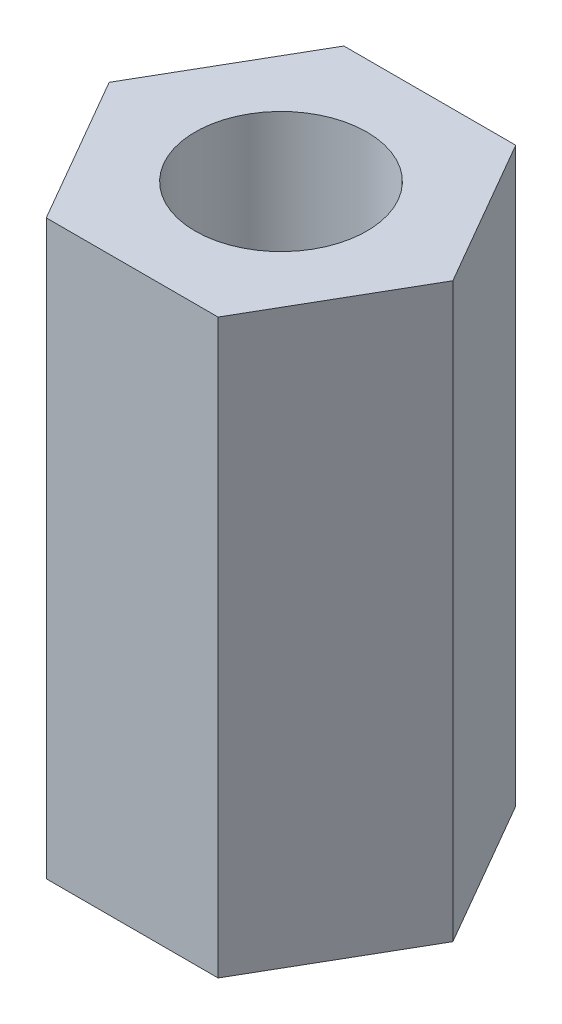
SolidWorks part; units mm, degrees
ref_plane "정면" through (0, 0, 0) normal (0, 0, 1) x (1, 0, 0)
ref_plane "윗면" through (0, 0, 0) normal (0, 1, 0) x (1, 0, 0)
ref_plane "우측면" through (0, 0, 0) normal (1, 0, 0) x (0, 0, -1)
sketch "스케치1" plane through (0, 0, 0) normal (0, 1, 0) x (1, 0, 0)
  line L1 (1.5011, 2.6) -> (-1.5011, 2.6)
  line L2 (-1.5011, 2.6) -> (-3.0022, 0)
  line L3 (-3.0022, 0) -> (-1.5011, -2.6)
  line L4 (-1.5011, -2.6) -> (1.5011, -2.6)
  line L5 (1.5011, -2.6) -> (3.0022, 0)
  line L6 (3.0022, 0) -> (1.5011, 2.6)
  circle A0 centre (0, 0) radius 2.6 construction
  circle A1 centre (0, 0) radius 1.5
  dimension "D2" = 3
  dimension "D1" = 5.2
extrude "보스-돌출1" add sketch "스케치1" along normal blind 10
